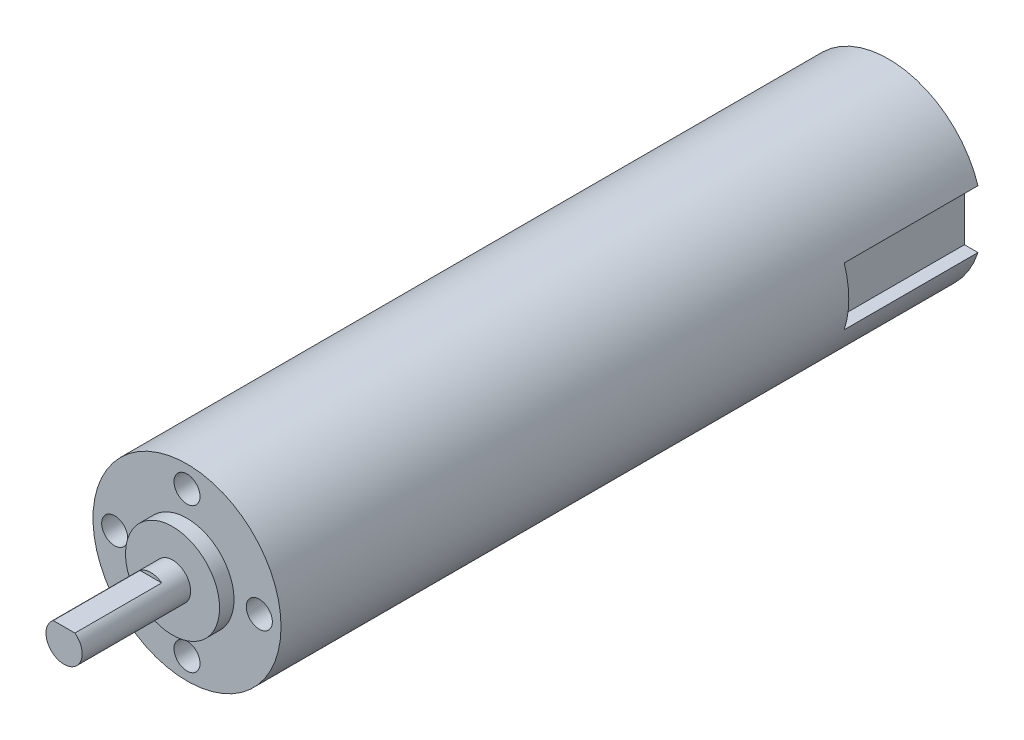
SolidWorks part; units mm, degrees
ref_plane "Plan de face" through (0, 0, 0) normal (0, 0, 1) x (1, 0, 0)
ref_plane "Plan de dessus" through (0, 0, 0) normal (0, 1, 0) x (1, 0, 0)
ref_plane "Plan de droite" through (0, 0, 0) normal (1, 0, 0) x (0, 0, -1)
sketch "Esquisse1" plane through (0, 0, 0) normal (0, 0, 1) x (1, 0, 0)
  circle A0 centre (0, 0) radius 13
  dimension "D1" = 26
extrude "Boss.-Extru.1" add sketch "Esquisse1" along normal blind 97
sketch "Esquisse2" plane through (0, 0, 97) normal (0, 0, 1) x (1, 0, 0)
  circle A0 centre (0, 0) radius 2.5
  dimension "D1" = 5
extrude "Boss.-Extru.2" add sketch "Esquisse2" along normal blind 17
sketch "Esquisse3" plane through (0, 0, 0) normal (0, 0, -1) x (-1, 0, 0)
  line L0 (-10.5, 0) -> (-10.5, 4)
  line L1 (10.5, 0) -> (13, 0) construction
  line L2 (-13, 0) -> (-10.5, 0) construction
  line L3 (-10.5, 4) -> (-12.3693, 4)
  line L4 (-10.5, 0) -> (-10.5, -4)
  line L5 (10.5, 0) -> (10.5, 4)
  line L6 (10.5, 4) -> (12.3693, 4)
  line L7 (10.5, 0) -> (10.5, -4)
  line L8 (10.5, -4) -> (12.365, -4.0133)
  line L9 (-10.5, -4) -> (-12.3693, -4)
  circle A0 centre (0, 0) radius 13 construction
  arc A1 (-12.3693, 4) -> (-12.3693, -4) centre (0, 0) ccw
  arc A2 (12.3693, 4) -> (12.365, -4.0133) centre (0, 0) cw
extrude "Enlèv. mat.-Extru.1" cut sketch "Esquisse3" against normal blind 18.5
sketch "Esquisse4" plane through (0, 0, 97) normal (0, 0, 1) x (1, 0, 0)
  circle A0 centre (0, 0) radius 6.5
  circle A1 centre (0, 0) radius 2.5
extrude "Boss.-Extru.3" add sketch "Esquisse4" along normal blind 2
sketch "Esquisse5" plane through (0, 0, 97) normal (0, 0, 1) x (1, 0, 0)
  line L0 (0, 0) -> (10, 0) construction
  line L1 (0, 0) -> (0, 10) construction
  line L2 (0, 0) -> (-10, 0) construction
  line L3 (0, 0) -> (0, -10) construction
  circle A0 centre (0, 10) radius 1.8
  circle A1 centre (-10, 0) radius 1.8
  circle A2 centre (0, -10) radius 1.8
  circle A3 centre (10, 0) radius 1.8
extrude "Enlèv. mat.-Extru.2" cut sketch "Esquisse5" against normal blind 4
sketch "Esquisse6" plane through (0, 0, 114) normal (0, 0, 1) x (1, 0, 0)
  line L0 (0, -2.5) -> (0, 2) construction
  line L1 (0, 2) -> (1.5, 2)
  line L2 (0, 2) -> (-1.5, 2)
  circle A2 centre (0, 0) radius 2.5 construction
  circle A3 centre (0, 0) radius 2.5 construction
  arc A4 (-1.5, 2) -> (1.5, 2) centre (0, 0) cw
extrude "Enlèv. mat.-Extru.3" cut sketch "Esquisse6" against normal blind 12
sketch "Esquisse7" plane through (0, 0, 97) normal (0, 0, 1) x (1, 0, 0)
  circle A0 centre (0, 0) radius 2.4968
extrude "Boss.-Extru.4" add sketch "Esquisse7" along normal blind 3 separate body
sketch "Esquisse8" plane through (0, 0, 100) normal (0, 0, 1) x (1, 0, 0)
  circle A0 centre (0, 0) radius 2.5
